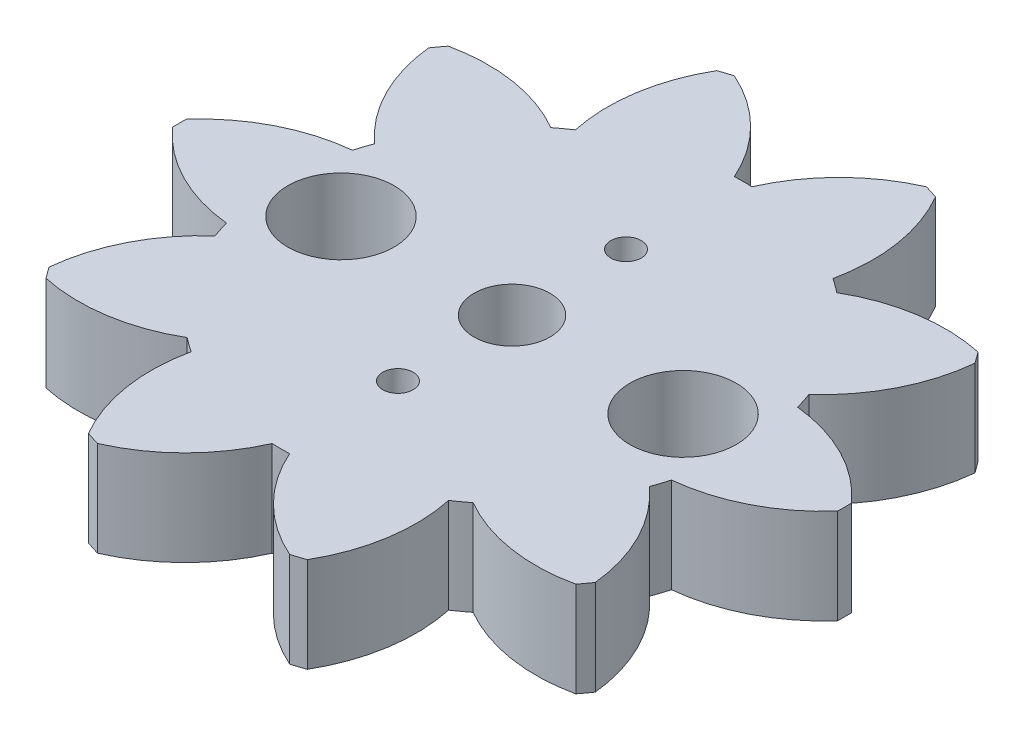
SolidWorks part; units mm, degrees
ref_plane "Front" through (0, 0, 0) normal (0, 0, 1) x (1, 0, 0)
ref_plane "Top" through (0, 0, 0) normal (0, 1, 0) x (1, 0, 0)
ref_plane "Right" through (0, 0, 0) normal (1, 0, 0) x (0, 0, -1)
sketch "Sketch1" plane through (0, 0, 0) normal (0, 1, 0) x (1, 0, 0)
  line L0 (0, 0) -> (0, 17.5) construction
  circle A0 centre (0, 0) radius 17.5
  dimension "D1" = 35
extrude "Boss-Extrude1" add sketch "Sketch1" along normal blind 5
sketch "Sketch2" plane through (0, 5, 0) normal (0, 1, 0) x (1, 0, 0)
  line L0 (0, 17.5) -> (0, 0) construction
  line L1 (0, 0) -> (-1.9266, 14.4555) construction
  line L2 (-4.5833, 16.8891) -> (0, 0) construction
  circle A0 centre (0, 0) radius 12.1705 construction
  circle A1 centre (0, 0) radius 14.5833 construction
  circle A3 centre (0, 0) radius 17.5 construction
  arc A4 (-0.4614, 12.1617) -> (-5.0577, 16.7532) centre (-8.6914, 8.5194) ccw
  arc A5 (0.4614, 12.1617) -> (-0.4614, 12.1617) centre (0, 0) ccw
  arc A6 (5.0577, 16.7532) -> (-5.0577, 16.7532) centre (0, 0) ccw
  arc A8 (0.4614, 12.1617) -> (5.0577, 16.7532) centre (8.6914, 8.5194) cw
  arc A9 (-5.75, 10.7265) -> (-4.1053, 17.0117) centre (3.1923, 11.7443) cw construction
  dimension "D1" = 35
  dimension "D2" = 29.1667
  dimension "D3" = 24.3409
  dimension "D4" = 9.163
  dimension "D5" = 9
extrude "Cut-Extrude1" cut sketch "Sketch2" against normal up to surface (5 mm away) up to face at (0, 0, 17.5)
pattern_circular "CirPattern1" count 10 over 360 about axis through (0, 0, 0) along (0, 1, 0) of "Cut-Extrude1"
sketch "Sketch3" plane through (0, 5, 0) normal (0, 1, 0) x (1, 0, 0)
  circle A0 centre (0, 0) radius 2
  dimension "D1" = 4
extrude "Cut-Extrude2" cut sketch "Sketch3" against normal up to surface (5 mm away) up to face at (0, 0, 0)
sketch "Sketch4" plane through (0, 5, 0) normal (0, 1, 0) x (1, 0, 0)
  line L0 (0, 0) -> (0, 6) construction
  line L1 (0, 0) -> (0, -6) construction
  line L2 (0, 0) -> (-9, 0) construction
  line L3 (0, 0) -> (9, 0) construction
  circle A0 centre (0, 6) radius 0.8
  circle A1 centre (0, -6) radius 0.8
  circle A4 centre (-9, 0) radius 2.8
  circle A5 centre (9, 0) radius 2.8
  dimension "D2" = 1.6
  dimension "D4" = 5.6
  dimension "D1" = 6
  dimension "D3" = 9
extrude "Cut-Extrude3" cut sketch "Sketch4" against normal blind 5
equation "\"od\" = 35'outside diameter"
equation "\"n\"= 10'number of teeth"
equation "\"m\"= \"od\" / ( \"n\" + 2 )'module"
equation "\"p\"= \"m\" * pi'pitch"
equation "\"d\"= \"m\" * \"n\"'primitive diameter"
equation "\"da\"= \"d\" + 2 * \"m\"'head diamater"
equation "\"df\"= \"d\" - 2 * \"m\"'foot diameter"
equation "\"D1@Sketch1\"=\"da\""
equation "\"D1@Sketch2\"=\"da\""
equation "\"D2@Sketch2\"=\"d\""
equation "\"D4@Sketch2\"=\"p\""
equation "\"D1@CirPattern1\"=\"n\""
